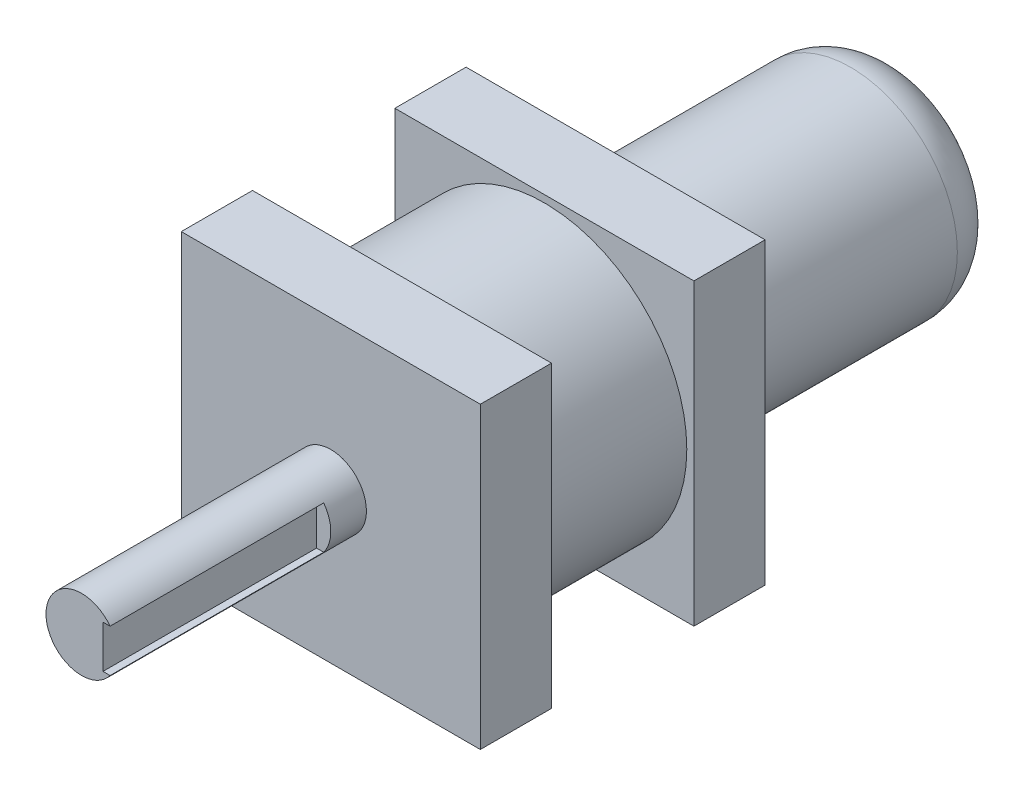
SolidWorks part; units mm, degrees
ref_plane "Front Plane" through (0, 0, 0) normal (0, 0, 1) x (1, 0, 0)
ref_plane "Top Plane" through (0, 0, 0) normal (0, 1, 0) x (1, 0, 0)
ref_plane "Right Plane" through (0, 0, 0) normal (1, 0, 0) x (0, 0, -1)
sketch "Sketch1" plane through (0, 0, 0) normal (0, 0, 1) x (1, 0, 0)
  circle A0 centre (0, 0) radius 15
  dimension "D1" = 30
extrude "Boss-Extrude1" add sketch "Sketch1" along normal blind 40
sketch "Sketch2" plane through (0, 0, 40) normal (0, 0, 1) x (1, 0, 0)
  line L1 (-21, 21) -> (21, 21)
  line L2 (-21, 21) -> (-21, -21)
  line L3 (-21, -21) -> (21, -21)
  line L4 (21, 21) -> (21, -21)
  line L5 (-21, 21) -> (21, -21) construction
  line L6 (-21, -21) -> (21, 21) construction
  point P0 (0, 0)
  dimension "D1" = 42
  dimension "D2" = 42
extrude "Boss-Extrude4" add sketch "Sketch2" along normal blind 10
sketch "Sketch3" plane through (0, 0, 50) normal (0, 0, 1) x (1, 0, 0)
  circle A0 centre (0, 0) radius 20
  dimension "D1" = 40
extrude "Boss-Extrude5" add sketch "Sketch3" along normal blind 20
sketch "Sketch4" plane through (0, 0, 70) normal (0, 0, 1) x (1, 0, 0)
  line L1 (-21, 21) -> (21, 21)
  line L2 (-21, 21) -> (-21, -21)
  line L3 (-21, -21) -> (21, -21)
  line L4 (21, 21) -> (21, -21)
  line L5 (-21, 21) -> (21, -21) construction
  line L6 (-21, -21) -> (21, 21) construction
  point P0 (0, 0)
extrude "Boss-Extrude6" add sketch "Sketch4" along normal blind 10
sketch "Sketch5" plane through (0, 0, 80) normal (0, 0, 1) x (1, 0, 0)
  circle A0 centre (0, 0) radius 5
  dimension "D1" = 10
extrude "Boss-Extrude7" add sketch "Sketch5" along normal blind 35
fillet "Fillet3" radius 7 1 edges at (15, 0, 0)
sketch "Sketch6" plane through (0, 0, 0) normal (0, 0, -1) x (-1, 0, 0)
  circle A0 centre (0, 0) radius 1.25
  dimension "D1" = 2.5
extrude "Boss-Extrude8" add sketch "Sketch6" along normal blind 5
fillet "Fillet5" radius 0.3 1 edges at (-1.25, 0, -5)
sketch "Sketch7" plane through (0, 0, 115) normal (0, 0, 1) x (1, 0, 0)
  line L1 (3, 3) -> (7, 3)
  line L2 (3, 3) -> (3, -3)
  line L3 (3, -3) -> (7, -3)
  line L4 (7, 3) -> (7, -3)
  line L5 (3, 3) -> (7, -3) construction
  line L6 (3, -3) -> (7, 3) construction
  circle A0 centre (0, 0) radius 5 construction
  circle A1 centre (0, 0) radius 5 construction
  point P0 (5, 0)
  dimension "D1" = 6
  dimension "D2" = 4
extrude "Cut-Extrude1" cut sketch "Sketch7" against normal blind 30
